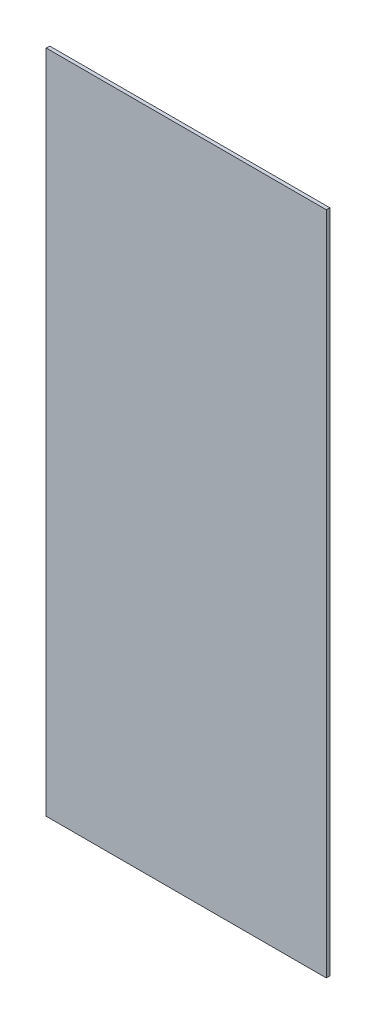
SolidWorks part; units mm, degrees
ref_plane "Plan de face" through (0, 0, 0) normal (0, 0, 1) x (1, 0, 0)
ref_plane "Plan de dessus" through (0, 0, 0) normal (0, 1, 0) x (1, 0, 0)
ref_plane "Plan de droite" through (0, 0, 0) normal (1, 0, 0) x (0, 0, -1)
sketch "Esquisse1" plane through (0, 0, 0) normal (0, 0, 1) x (1, 0, 0)
  line L1 (0, 0) -> (40, 0)
  line L2 (0, 0) -> (0, 95)
  line L3 (0, 95) -> (40, 95)
  line L4 (40, 0) -> (40, 95)
  dimension "D1" = 40
  dimension "D2" = 95
extrude "Boss.-Extru.1" add sketch "Esquisse1" along normal blind 0.5
